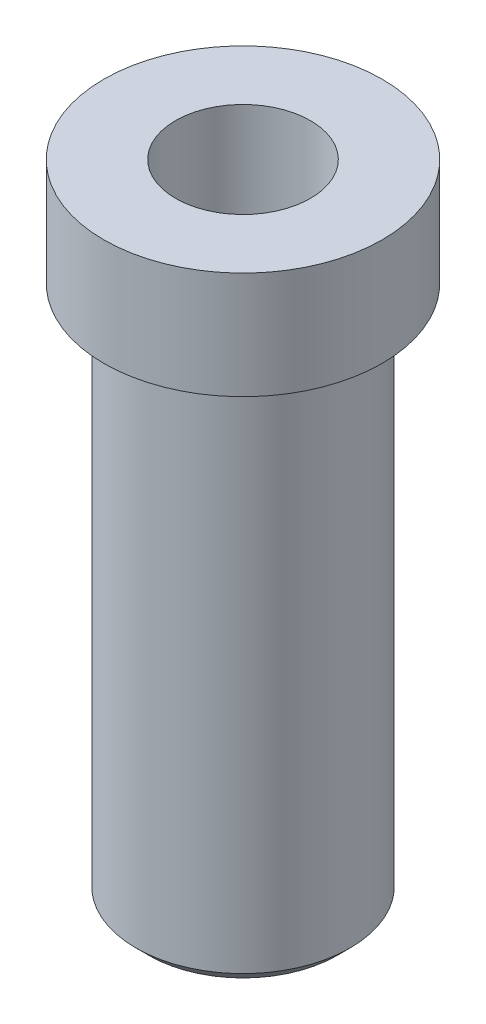
SolidWorks part; units mm, degrees
ref_plane "Front Plane" through (0, 0, 0) normal (0, 0, 1) x (1, 0, 0)
ref_plane "Top Plane" through (0, 0, 0) normal (0, 1, 0) x (1, 0, 0)
ref_plane "Right Plane" through (0, 0, 0) normal (1, 0, 0) x (0, 0, -1)
sketch "Sketch1" plane through (0, 0, 0) normal (0, 0, 1) x (1, 0, 0)
  line L0 (0, 38.1) -> (0, -38.1) construction
  line L1 (-27.3369, 0) -> (14.165, 0) construction
  line L2 (12.7, -38.1) -> (12.7, 25.4)
  line L3 (12.7, 25.4) -> (16.51, 25.4)
  line L4 (16.51, 25.4) -> (16.51, 38.1)
  line L5 (16.51, 38.1) -> (8.001, 38.1)
  line L6 (8.001, 38.1) -> (8.001, -38.1)
  line L7 (8.001, -38.1) -> (12.7, -38.1)
  point P10 (0, 0)
  point P12 (14.165, 0)
  point P13 (2.3885, 39.5104)
  point P14 (16.51, 31.75)
  dimension "D1" = 76.2
  dimension "D2" = 63.5
  dimension "D3" = 12.7
  dimension "D4" = 33.02
  dimension "D5" = 16.002
  dimension "D6" = 25.4
  dimension "D7" = 38.1
revolve "Revolve2" add sketch "Sketch1" angle 360 about L0
chamfer "Chamfer1" distance 1.524 angle 45 1 edges at (-12.7, -38.1, 0)
